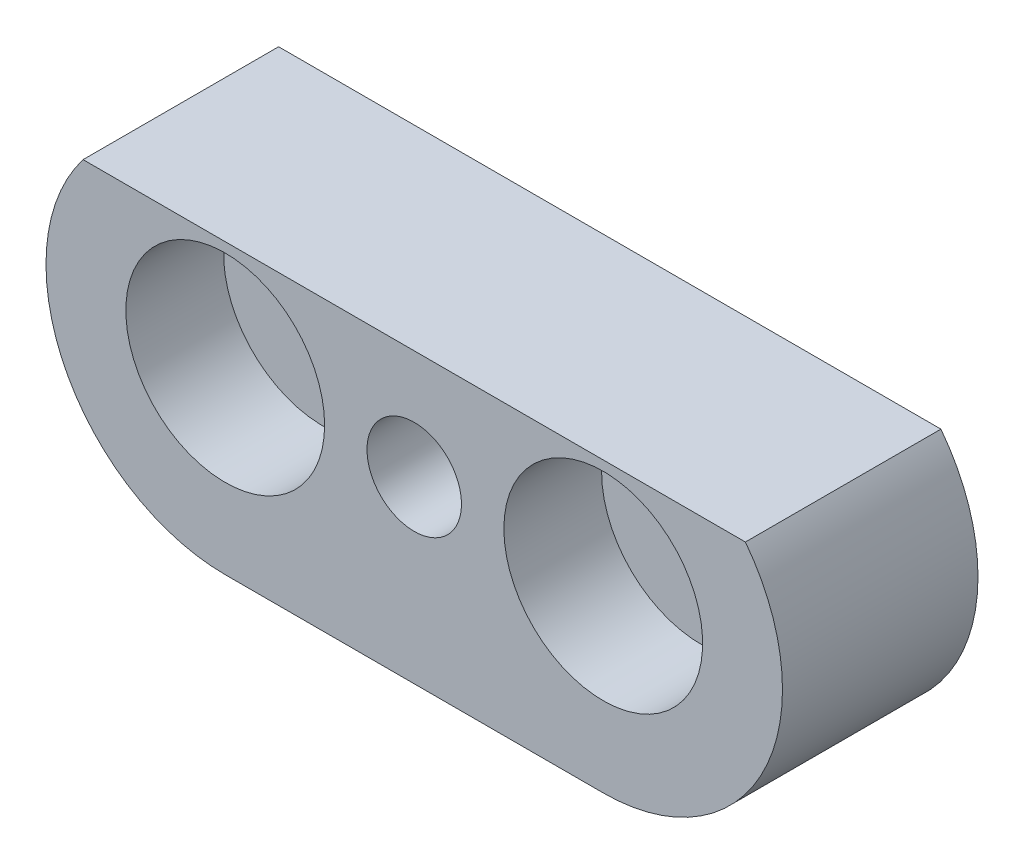
SolidWorks part; units mm, degrees
ref_plane "Front Plane" through (0, 0, 0) normal (0, 0, 1) x (1, 0, 0)
ref_plane "Top Plane" through (0, 0, 0) normal (0, 1, 0) x (1, 0, 0)
ref_plane "Right Plane" through (0, 0, 0) normal (1, 0, 0) x (0, 0, -1)
sketch "Sketch1" plane through (0, 0, 0) normal (0, 0, 1) x (1, 0, 0)
  circle A0 centre (-5.8, 3.35) radius 3.5
  dimension "D1" = 7
extrude "Extrude-Thin1" add sketch "Sketch1" along normal blind 2 thin thin type one direction reverse wall 0.4
mirror "Mirror3" about plane through (0, 0, 0) normal (1, 0, 0) of bodies 101
sketch "Sketch2" plane through (0, 0, 2) normal (0, 0, 1) x (1, 0, 0)
  line L0 (-5.8, 3.35) -> (5.8, 3.35) construction
  line L1 (-5.8, 6.85) -> (5.8, 6.85)
  line L2 (-5.8, -0.15) -> (5.8, -0.15)
  arc A0 (-5.8, 6.85) -> (-5.8, -0.15) centre (-5.8, 3.35) ccw
  arc A1 (5.8, -0.15) -> (5.8, 6.85) centre (5.8, 3.35) ccw
  circle A2 centre (5.8, 3.35) radius 3.5 construction
  point P4 (0, 3.35)
extrude "Boss-Extrude1" add sketch "Sketch2" along normal blind 4
sketch "Sketch3" plane through (0, 0, 6) normal (0, 0, 1) x (1, 0, 0)
  circle A0 centre (-5.8, 3.35) radius 3.05
  dimension "D1" = 6.1
extrude "Cut-Extrude1" cut sketch "Sketch3" against normal blind 3
mirror "Mirror4" about plane through (0, 0, 0) normal (1, 0, 0) of "Cut-Extrude1"
sketch "Sketch4" plane through (0, 0, 6) normal (0, 0, 1) x (1, 0, 0)
  line L0 (0, 3.35) -> (5.8, 3.35) construction
  circle A0 centre (0, 3.35) radius 1.45
  dimension "D1" = 2.9
extrude "Cut-Extrude2" cut sketch "Sketch4" against normal up to next
sketch "Sketch5" plane through (0, 0, 2) normal (0, 0, -1) x (-1, 0, 0)
  line L2 (-5.8, -0.15) -> (5.8, -0.15)
  line L3 (5.8, 6.85) -> (-5.8, 6.85)
  line L4 (-5.8, -0.15) -> (5.8, -0.15)
  line L5 (5.8, 6.85) -> (-5.8, 6.85)
  circle A0 centre (0, 3.35) radius 1.45 construction
  circle A1 centre (0, 3.35) radius 1.45
  arc A4 (-5.8, -0.15) -> (-5.8, 6.85) centre (-5.8, 3.35) ccw
  arc A5 (5.8, 6.85) -> (5.8, -0.15) centre (5.8, 3.35) ccw
  arc A7 (5.8, 6.85) -> (5.8, -0.15) centre (5.8, 3.35) ccw
  arc A9 (-5.8, -0.15) -> (-5.8, 6.85) centre (-5.8, 3.35) ccw
  dimension "D1" = 0
extrude "Boss-Extrude2" add sketch "Sketch5" along normal up to surface (2 mm away)
fillet "Fillet1" radius 1 2 edges at (-2.7, 3.35, 2) (2.7, 3.35, 2)
sketch "Sketch6" plane through (0, 0, 6) normal (0, 0, 1) x (1, 0, 0)
  line L2 (-5.8, -0.15) -> (5.8, -0.15)
  line L3 (5.8, 6.85) -> (-5.8, 6.85)
  line L4 (-5.8, -0.15) -> (5.8, -0.15)
  line L5 (5.8, 6.85) -> (-5.8, 6.85)
  arc A2 (-5.8, 6.85) -> (-5.8, -0.15) centre (-5.8, 3.35) ccw
  arc A3 (5.8, -0.15) -> (5.8, 6.85) centre (5.8, 3.35) ccw
  arc A4 (-5.8, 6.85) -> (-5.8, -0.15) centre (-5.8, 3.35) ccw
  arc A5 (5.8, -0.15) -> (5.8, 6.85) centre (5.8, 3.35) ccw
  dimension "D1" = 0
extrude "Extrude-Thin2" add sketch "Sketch6" against normal up to surface (6 mm away) thin
sketch "Sketch7" plane through (0, 0, 6) normal (0, 0, 1) x (1, 0, 0)
  line L0 (-10.1621, 6.7) -> (10.1621, 6.7)
  line L1 (-12.5, 7.2) -> (12.5, 7.2) construction
  line L2 (-5.8, -2.15) -> (5.8, -2.15)
  line L3 (5.8, 8.85) -> (-5.8, 8.85)
  line L5 (5.8, 8.85) -> (-5.8, 8.85)
  arc A2 (-5.8, 8.85) -> (-5.8, -2.15) centre (-5.8, 3.35) ccw
  arc A3 (5.8, -2.15) -> (5.8, 8.85) centre (5.8, 3.35) ccw
  arc A4 (-5.8, 8.85) -> (-10.1621, 6.7) centre (-5.8, 3.35) ccw
  arc A5 (10.1621, 6.7) -> (5.8, 8.85) centre (5.8, 3.35) ccw
  dimension "D2" = 0.5
  dimension "D1" = 0
extrude "Cut-Extrude3" cut sketch "Sketch7" against normal up to next
